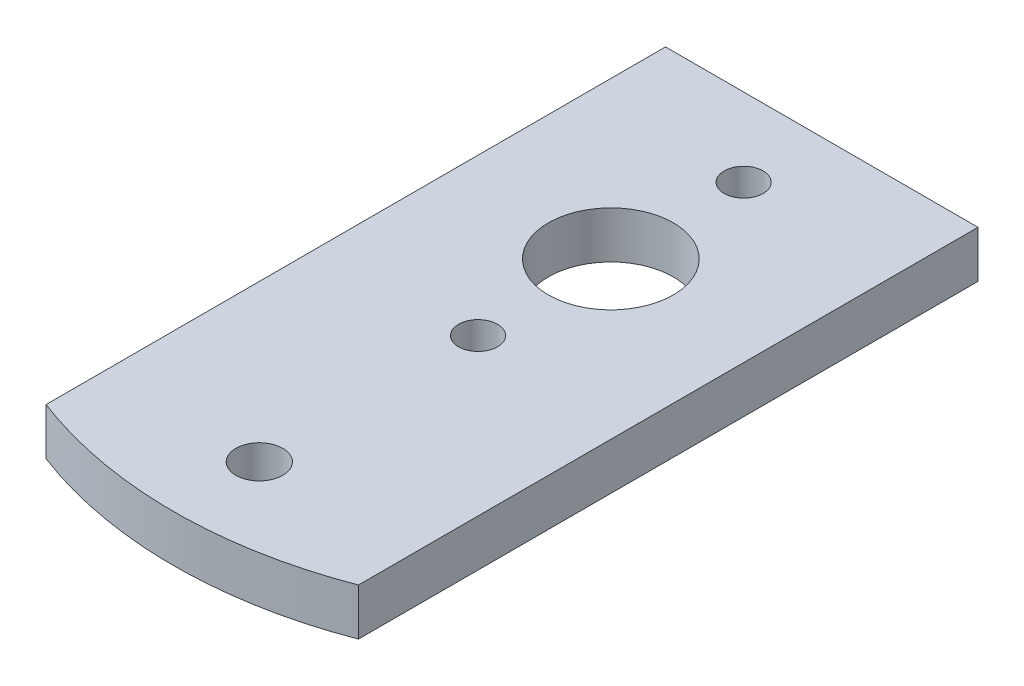
SolidWorks part; units mm, degrees
ref_plane "Front Plane" through (0, 0, 0) normal (0, 0, 1) x (1, 0, 0)
ref_plane "Top Plane" through (0, 0, 0) normal (0, 1, 0) x (1, 0, 0)
ref_plane "Right Plane" through (0, 0, 0) normal (1, 0, 0) x (0, 0, -1)
sketch "Sketch1" plane through (0, 0, 0) normal (0, 1, 0) x (1, 0, 0)
  line L0 (0, 0) -> (0, 1) construction
  line L1 (-10, -23) -> (10, -23)
  line L2 (-10, -23) -> (-10, 23)
  line L3 (-10, 23) -> (10, 23)
  line L4 (10, -23) -> (10, 23)
  line L5 (-10, -23) -> (10, 23) construction
  line L6 (-10, 23) -> (10, -23) construction
  line L7 (0, 1) -> (0, 18) construction
  line L8 (0, 0) -> (0, -13) construction
  circle A0 centre (0, 18) radius 1.25
  circle A1 centre (0, 1) radius 1.25
  circle A2 centre (0, 9.5) radius 4
  circle A3 centre (0, -13) radius 1.5
  point P0 (0, 0)
  dimension "D5" = 2.5
  dimension "D6" = 2.5
  dimension "D7" = 8
  dimension "D8" = 3
  dimension "D9" = 22.5
  dimension "D1" = 20
  dimension "D2" = 46
  dimension "D3" = 17
  dimension "D4" = 1
extrude "Boss-Extrude1" add sketch "Sketch1" along normal blind 3
sketch "Sketch2" plane through (0, 3, 0) normal (0, 1, 0) x (1, 0, 0)
  line L0 (0, -0.25) -> (0, -16.6534) construction
  line L1 (10, -16.6534) -> (-10, -16.6534)
  line L2 (-10, -16.6534) -> (-10, -36.6534)
  line L3 (-10, -36.6534) -> (10, -36.6534)
  line L4 (10, -16.6534) -> (10, -36.6534)
  line L6 (-10, 23) -> (-10, -23) construction
  circle A0 centre (0, 1) radius 1.25 construction
  circle A2 centre (0, 9.5) radius 28
  point P9 (0, -36.6534)
  point P13 (-10, -18.7843)
  point P14 (0, 0)
  point P15 (0, 0)
  line M5 (-10, 23) -> (-10, -23)
  line M8 (10, -23) -> (10, 23)
  line M15 (-10, -23) -> (10, -23)
  dimension "D2" = 56
  dimension "D1" = 20
extrude "Cut-Extrude4" cut sketch "Sketch2" against normal through all contours L4 L2 L3 M15 | A2 M5 M15 M8
